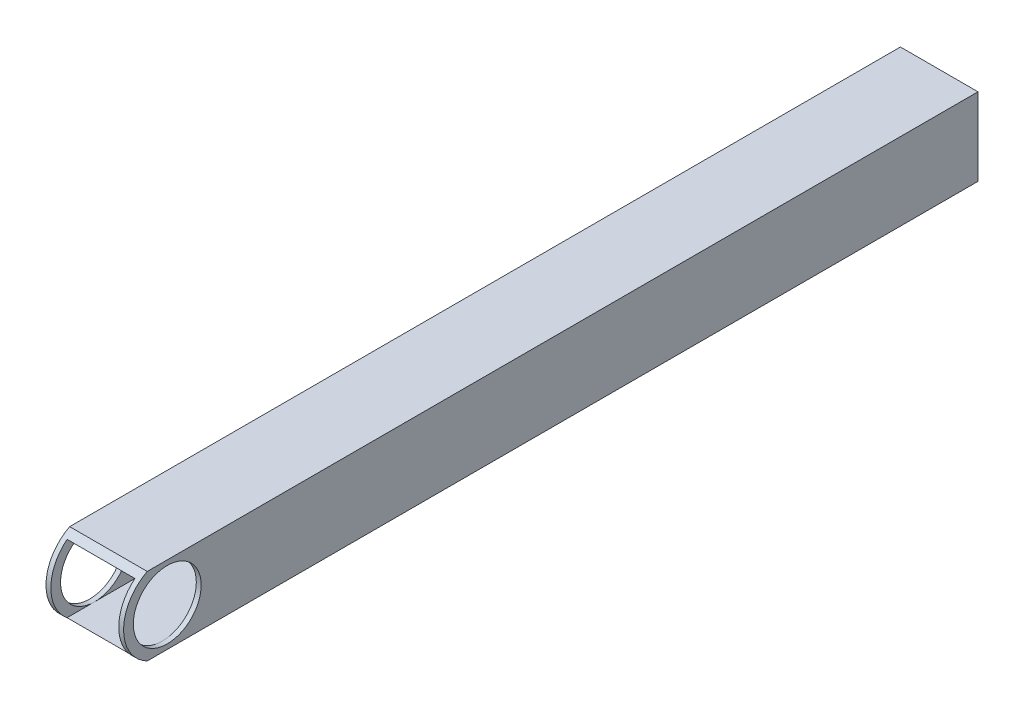
SolidWorks part; units mm, degrees
material "6061 Alloy"
ref_plane "Front Plane" through (0, 0, 0) normal (0, 0, 1) x (1, 0, 0)
ref_plane "Top Plane" through (0, 0, 0) normal (0, 1, 0) x (1, 0, 0)
ref_plane "Right Plane" through (0, 0, 0) normal (1, 0, 0) x (0, 0, -1)
sketch "Sketch1" plane through (0, 0, 0) normal (0, 0, 1) x (1, 0, 0)
  line L1 (12.7, -12.7) -> (-12.7, -12.7)
  line L2 (12.7, -12.7) -> (12.7, 12.7)
  line L3 (12.7, 12.7) -> (-12.7, 12.7)
  line L4 (-12.7, -12.7) -> (-12.7, 12.7)
  line L5 (12.7, -12.7) -> (-12.7, 12.7) construction
  line L6 (12.7, 12.7) -> (-12.7, -12.7) construction
  point P0 (0, 0)
  dimension "D1" = 25.4
extrude "Extrude-Thin1" add sketch "Sketch1" along normal mid plane 284.48 thin
sketch "Sketch2" plane through (12.7, 0, 0) normal (1, 0, 0) x (0, 0, -1)
  line L0 (-142.24, -12.7) -> (-142.24, 12.7) construction
  line L1 (-142.24, -12.7) -> (142.24, -12.7) construction
  circle A0 centre (-123.19, 0) radius 11.1125
  dimension "D1" = 22.225
  dimension "D2" = 19.05
  dimension "D3" = 12.7
extrude "Cut-Extrude1" cut sketch "Sketch2" against normal through all
sketch "Sketch3" plane through (12.7, 0, 0) normal (1, 0, 0) x (0, 0, -1)
  line L0 (-123.19, 14.2875) -> (-142.24, 14.2875)
  line L3 (-142.24, 14.2875) -> (-142.24, -12.7)
  line L4 (-142.24, -12.7) -> (-129.7354, -12.7)
  arc A0 (-123.19, 14.2875) -> (-129.7354, -12.7) centre (-123.19, 0) ccw
  circle A1 centre (-123.19, 0) radius 11.1125 construction
  dimension "D1" = 3.175
extrude "Cut-Extrude2" cut sketch "Sketch3" against normal through all
